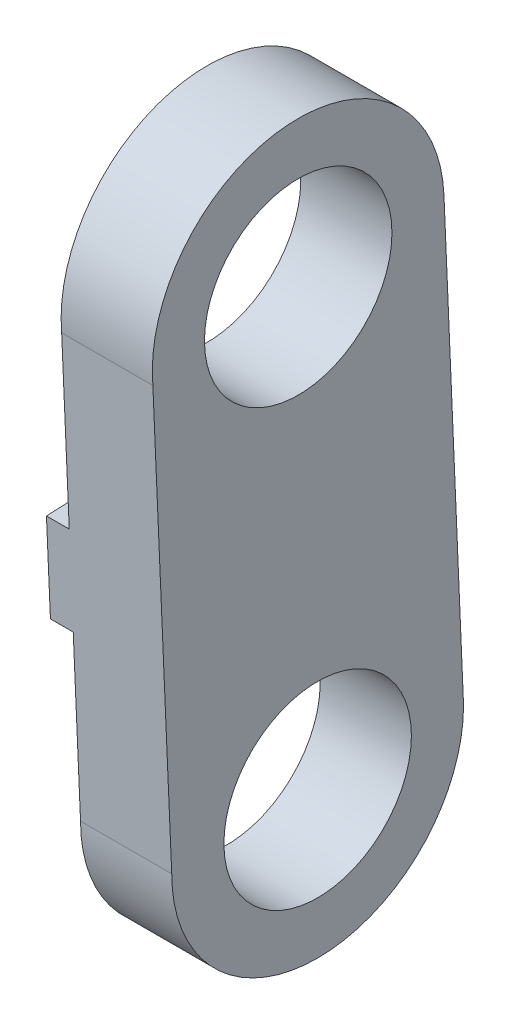
SolidWorks part; units mm, degrees
material "ABS"
ref_plane "Front Plane" through (0, 0, 0) normal (0, 0, 1) x (1, 0, 0)
ref_plane "Top Plane" through (0, 0, 0) normal (0, 1, 0) x (1, 0, 0)
ref_plane "Right Plane" through (0, 0, 0) normal (1, 0, 0) x (0, 0, -1)
sketch "Sketch1" plane through (0, 0, 0) normal (1, 0, 0) x (0, 0, -1)
  line L0 (0, 0) -> (177.8, 0) construction
  line L1 (0, 0) -> (177.1234, 15.4963) construction
  line L2 (172.0627, 15.0535) -> (172.72, 0)
  line L3 (177.1234, 15.4963) -> (187.6937, 16.4211) construction
  line L4 (182.1987, 15.7163) -> (182.88, 0)
  circle A0 centre (177.8, 0) radius 3.2639
  circle A1 centre (177.1234, 15.4963) radius 3.2639
  arc A2 (182.1987, 15.7163) -> (172.0627, 15.0535) centre (177.1234, 15.4963) ccw
  arc A3 (172.72, 0) -> (182.88, 0) centre (177.8, 0) ccw
  dimension "D2" = 6.5278
  dimension "D4" = 6.5278
  dimension "D6" = 10.16
  dimension "D7" = 10.16
  dimension "D1" = 177.8
  dimension "D3" = 5
  dimension "D5" = 177.8
extrude "Boss-Extrude1" add sketch "Sketch1" along normal blind 3.175
sketch "Sketch2" plane through (0, 0, 0) normal (-1, 0, 0) x (0, 0, 1)
  line L0 (-182.5393, 7.8582) -> (-172.3914, 7.5268) construction
  line L1 (-182.88, 0) -> (-182.1987, 15.7163) construction
  line L2 (-172.0627, 15.0535) -> (-172.72, 0) construction
  line L3 (-182.5393, 7.8582) -> (-182.6081, 6.2721)
  line L4 (-182.6081, 6.2721) -> (-172.4655, 5.8293)
  line L5 (-172.4655, 5.8293) -> (-172.3269, 9.0044)
  line L6 (-172.3269, 9.0044) -> (-182.4706, 9.4442)
  line L7 (-182.4706, 9.4442) -> (-182.5393, 7.8582)
  dimension "D1" = 1.5875
extrude "Boss-Extrude2" add sketch "Sketch2" along normal blind 0.7937
